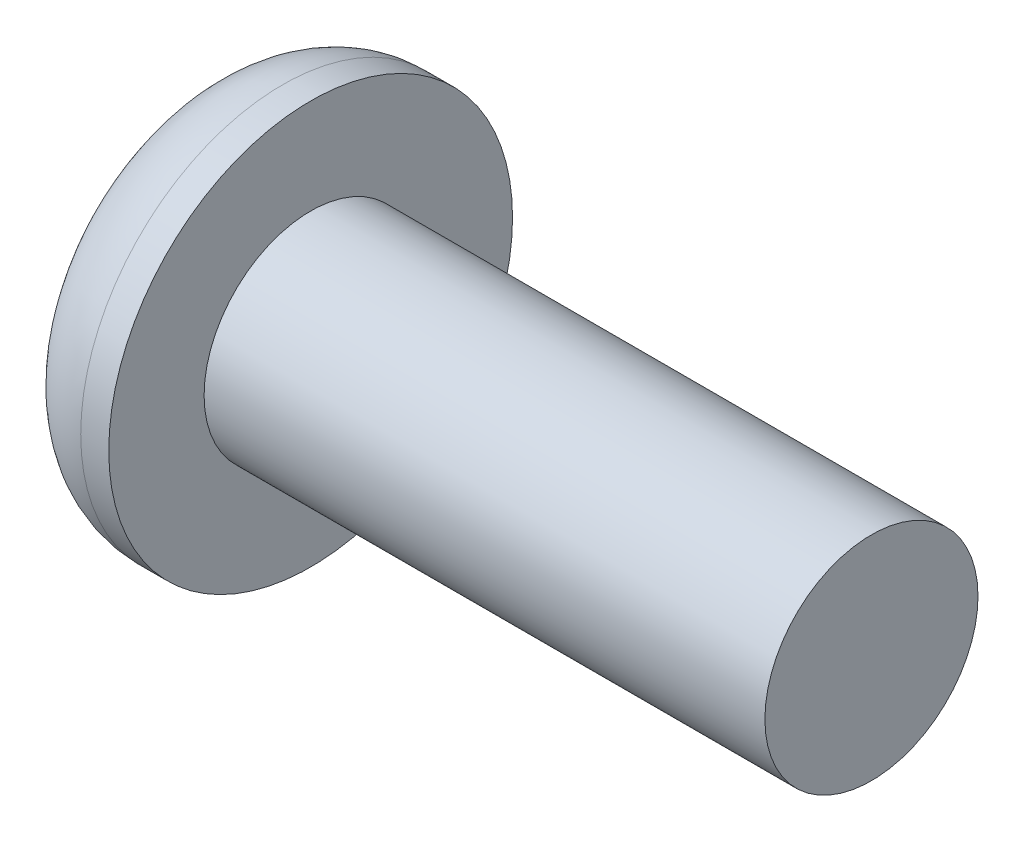
SolidWorks part; units mm, degrees
ref_plane "Front" through (0, 0, 0) normal (0, 0, 1) x (1, 0, 0)
ref_plane "Top" through (0, 0, 0) normal (0, 1, 0) x (1, 0, 0)
ref_plane "Right" through (0, 0, 0) normal (1, 0, 0) x (0, 0, -1)
sketch "Sketch1" plane through (0, 0, 0) normal (1, 0, 0) x (0, 0, -1)
  circle A0 centre (0, 0) radius 4.572
  dimension "D1" = 9.144
extrude "Boss-Extrude1" add sketch "Sketch1" along normal blind 2.54
sketch "Sketch2" plane through (2.54, 0, 0) normal (1, 0, 0) x (0, 0, -1)
  circle A0 centre (0, 0) radius 2.413
  dimension "D1" = 4.826
extrude "Boss-Extrude2" add sketch "Sketch2" along normal blind 12.7
fillet "Fillet1" radius 1.905 1 edges at (0, 0, -4.572)
sketch "Sketch3" plane through (0, 0, 0) normal (-1, 0, 0) x (0, 0, 1)
  line L1 (1.5736, -0.9402) -> (1.601, 0.8927)
  line L2 (1.601, 0.8927) -> (0.0274, 1.8329)
  line L3 (0.0274, 1.8329) -> (-1.5736, 0.9402)
  line L4 (-1.5736, 0.9402) -> (-1.601, -0.8927)
  line L5 (-1.601, -0.8927) -> (-0.0274, -1.8329)
  line L6 (-0.0274, -1.8329) -> (1.5736, -0.9402)
  circle A0 centre (0, 0) radius 1.5875 construction
extrude "Cut-Extrude1" cut sketch "Sketch3" against normal blind 1.905
ref_point "Point1"
